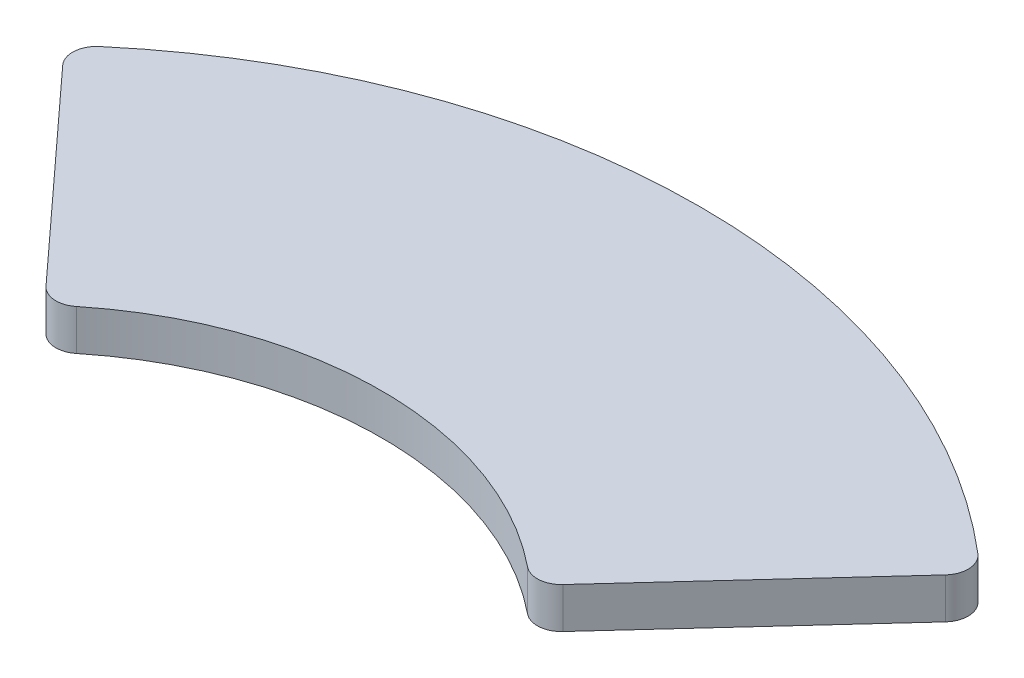
SolidWorks part; units mm, degrees
ref_plane "Front Plane" through (0, 0, 0) normal (0, 0, 1) x (1, 0, 0)
ref_plane "Top Plane" through (0, 0, 0) normal (0, 1, 0) x (1, 0, 0)
ref_plane "Right Plane" through (0, 0, 0) normal (1, 0, 0) x (0, 0, -1)
sketch "Sketch1" plane through (0, 0, 0) normal (0, 1, 0) x (1, 0, 0)
  line L0 (-10.1339, -10.5908) -> (-19.1192, -0.7851)
  line L1 (10.1339, -10.5908) -> (19.1192, -0.7851)
  arc A0 (-10.1339, -10.5908) -> (10.1339, -10.5908) centre (0, -21.65) cw
  arc A1 (-19.1192, -0.7851) -> (19.1192, -0.7851) centre (0, -21.65) cw
  arc A2 (0, 0) -> (-14.6265, -5.6879) centre (0, -21.65) ccw construction
  point P3 (0, 0)
  point P4 (13.0155, -11.7114)
  point P5 (-15.0499, -5.8526)
  point P7 (-20.4554, -1.3047)
  point P11 (0, -6.65)
  dimension "D3" = 15
  dimension "D1" = 13.3
  dimension "D2" = 85
extrude "Boss-Extrude1" add sketch "Sketch1" along normal mid plane 1.7
fillet "Fillet1" radius 1 4 edges at (19.1192, 0, 0.7851) (10.1339, 0, 10.5908) (-10.1339, 0, 10.5908) (-19.1192, 0, 0.7851)
